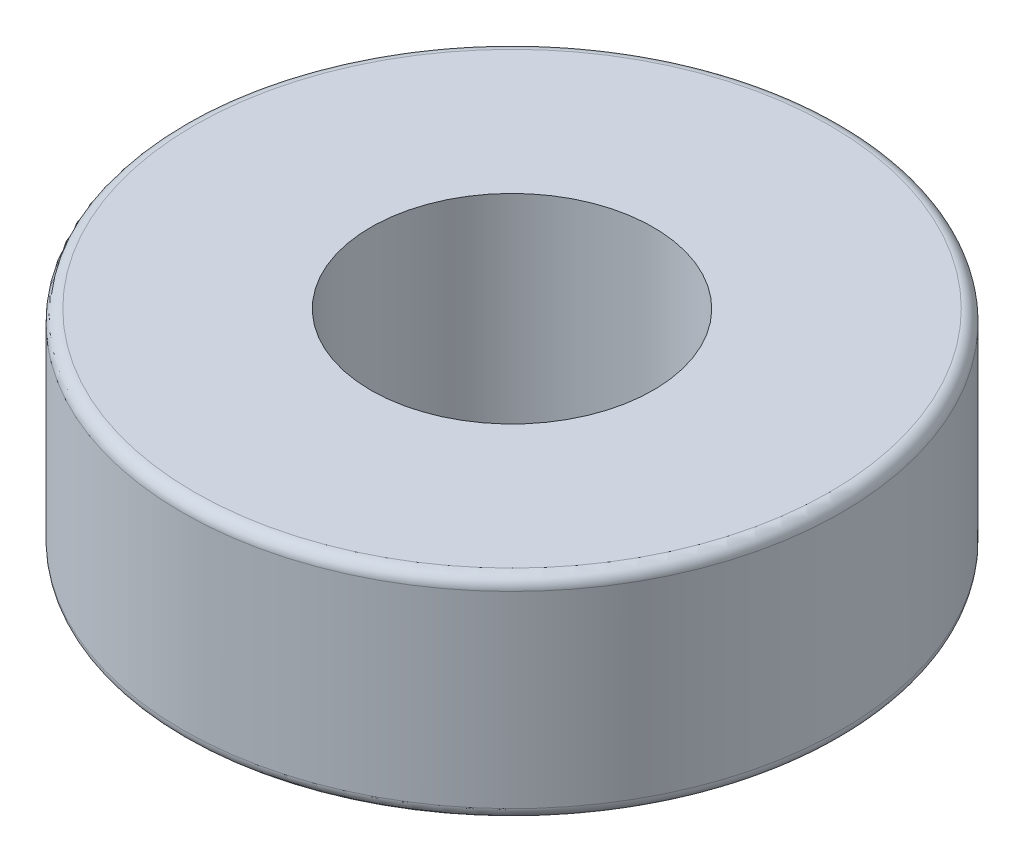
SolidWorks part; units mm, degrees
material "AISI 321 Annealed Stainless Steel (SS)"
ref_plane "Front Plane" through (0, 0, 0) normal (0, 0, 1) x (1, 0, 0)
ref_plane "Top Plane" through (0, 0, 0) normal (0, 1, 0) x (1, 0, 0)
ref_plane "Right Plane" through (0, 0, 0) normal (1, 0, 0) x (0, 0, -1)
sketch "Sketch2" plane through (0, 0, 0) normal (1, 0, 0) x (0, 0, -1)
  line L0 (0, 0) -> (0, -3.9783) construction
  line L1 (0, 0) -> (-11.1125, 0) construction
  line L2 (-11.1125, 3.571) -> (-11.1125, -3.571)
  line L3 (-11.1125, 3.571) -> (-4.7625, 3.571)
  line L4 (-4.7625, 3.571) -> (-4.7625, -3.571)
  line L5 (-4.7625, -3.571) -> (-11.1125, -3.571)
  point P9 (-11.1125, 0)
  dimension "D1" = 11.1125
  dimension "D2" = 4.7625
  dimension "D3" = 7.142
revolve "Revolve1" add sketch "Sketch2" angle 360 about L0
fillet "Fillet1" radius 0.4 2 edges at (0, 3.571, 11.1125) (0, -3.571, 11.1125)
